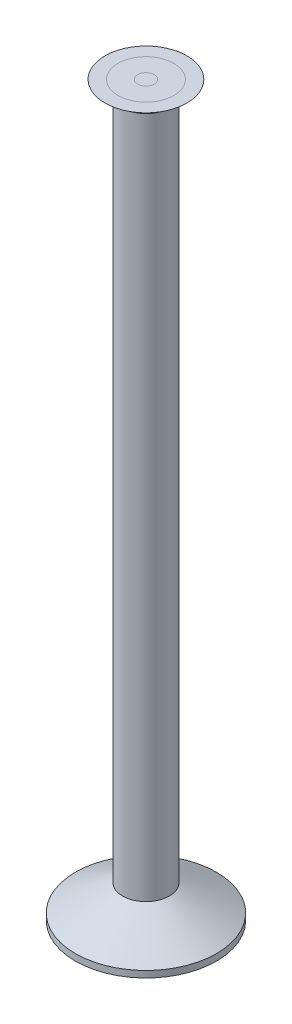
SolidWorks part; units mm, degrees
ref_plane "Alzado" through (0, 0, 0) normal (0, 0, 1) x (1, 0, 0)
ref_plane "Planta" through (0, 0, 0) normal (0, 1, 0) x (1, 0, 0)
ref_plane "Vista lateral" through (0, 0, 0) normal (1, 0, 0) x (0, 0, -1)
sketch "Croquis1" plane through (0, 0, 0) normal (0, 0, 1) x (1, 0, 0)
  line L0 (0, -22.5273) -> (0, 62.2297) construction
  line L1 (5.375, 0) -> (5.375, 0.5)
  line L2 (5.375, 0.5) -> (1.78, 2.5)
  line L3 (1.78, 2.5) -> (1.78, 54.5)
  line L4 (1.78, 54.5) -> (3.1196, 55.5)
  line L5 (3.1196, 55.5) -> (2.1252, 55.5)
  line L6 (1.375, 54.94) -> (1.375, 0)
  line L7 (1.375, 0) -> (5.375, 0)
  line L8 (0.375, 0) -> (0.375, 54.94)
  line L9 (0.6305, 55.5) -> (0, 55.5)
  line L10 (0.375, 0) -> (0, 0)
  line L11 (0, 55.5) -> (0, 0)
  line L14 (2.1252, 55.5) -> (1.375, 54.94)
  line L15 (2.1252, 55.5) -> (2.1253, 60.571) construction
  line L16 (0.6305, 55.1307) -> (0.375, 54.94)
  line L19 (0.6305, 55.5) -> (0.6305, 55.1307)
  dimension "D1" = 55
  dimension "D2" = 10.75
  dimension "D3" = 2
  dimension "D4" = 0.5
  dimension "D5" = 0.75
  dimension "D6" = 2.75
  dimension "D7" = 3.56
  dimension "D8" = 1
revolve "Revolución1" add sketch "Croquis1" angle 360 about L11
sketch "Croquis3" plane through (0, 0, 0) normal (0, 0, 1) x (1, 0, 0)
  line L0 (0, 55.5) -> (0, 0) construction
  line L6 (0.375, 54.94) -> (0.6305, 55.1307)
  line L7 (0.375, 0) -> (0.375, 54.94)
  line L8 (0, 0) -> (0.375, 0)
  line L9 (0, 55.5) -> (0, 0)
  line L10 (0.6305, 55.5) -> (0, 55.5)
  line L11 (0.6305, 55.1307) -> (0.6305, 55.5)
  line L12 (0.375, 54.94) -> (0.6305, 55.1307)
  line L13 (0.375, 0) -> (0.375, 54.94)
  line L16 (2.1252, 55.5) -> (0.6305, 55.5)
  line L17 (0.6305, 55.1307) -> (0.6305, 55.5)
  line L20 (3.1196, 55.5) -> (2.1252, 55.5)
  line L21 (1.78, 54.5) -> (3.1196, 55.5)
  line L22 (1.78, 2.5) -> (1.78, 54.5)
  line L23 (5.375, 0.5) -> (1.78, 2.5)
  line L24 (5.375, 0) -> (5.375, 0.5)
  line L25 (1.375, 0) -> (5.375, 0)
  line L26 (1.375, 54.94) -> (1.375, 0)
  line L27 (2.1252, 55.5) -> (1.375, 54.94)
  line L33 (0.375, 0) -> (1.375, 0)
  line L34 (1.375, 54.94) -> (1.375, 0)
  line L35 (2.1252, 55.5) -> (1.375, 54.94)
  dimension "D1" = 0
  dimension "D2" = 0
revolve "Revolución2" add sketch "Croquis3" angle 360 about L0
